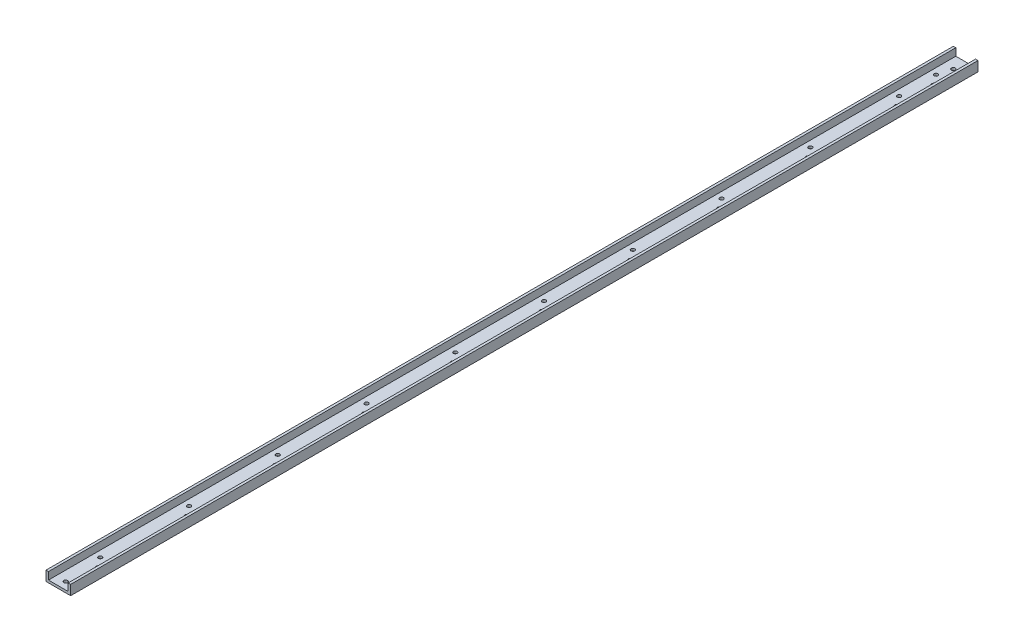
SolidWorks part; units mm, degrees
ref_plane "Front Plane" through (0, 0, 0) normal (0, 0, 1) x (1, 0, 0)
ref_plane "Top Plane" through (0, 0, 0) normal (0, 1, 0) x (1, 0, 0)
ref_plane "Right Plane" through (0, 0, 0) normal (1, 0, 0) x (0, 0, -1)
sketch "Sketch1" plane through (0, 0, 0) normal (0, 0, 1) x (1, 0, 0)
  line L0 (3.175, 3.175) -> (3.175, 12.7)
  line L1 (0, 0) -> (31.75, 0)
  line L2 (0, 0) -> (0, 12.7)
  line L4 (31.75, 0) -> (31.75, 12.7)
  line L5 (3.175, 3.175) -> (28.575, 3.175)
  line L6 (28.575, 3.175) -> (28.575, 12.7)
  line L7 (0, 12.7) -> (3.175, 12.7)
  line L8 (31.75, 12.7) -> (28.575, 12.7)
  dimension "D1" = 31.75
  dimension "D2" = 12.7
  dimension "D3" = 3.175
extrude "Boss-Extrude1" add sketch "Sketch1" along normal blind 1168.4
sketch "Sketch3" plane through (0, 3.175, 0) normal (0, 1, 0) x (1, 0, 0)
  line L0 (11.1125, -1109.6625) -> (11.1125, -1122.3625) construction
  line L1 (11.1125, -1122.3625) -> (20.6375, -1122.3625) construction
  line L2 (20.6375, -1122.3625) -> (11.1125, -1109.6625) construction
  line L3 (20.6375, -1122.3625) -> (20.6375, -1168.4) construction
  line L4 (28.575, -1168.4) -> (3.175, -1168.4) construction
  circle A1 centre (11.1125, -1109.6625) radius 2.413
  circle A3 centre (20.6375, -1122.3625) radius 2.413
  dimension "D1" = 9.525
  dimension "D2" = 12.7
  dimension "D3" = 46.0375
extrude "Cut-Extrude1" cut sketch "Sketch3" against normal up to next
sketch "Sketch4" plane through (0, 3.175, 0) normal (0, 1, 0) x (1, 0, 0)
  line L0 (15.875, -1168.4) -> (15.875, -1158.875) construction
  line L1 (28.575, -1168.4) -> (3.175, -1168.4) construction
  circle A0 centre (15.875, -1158.875) radius 2.413
  dimension "D2" = 4.826
  dimension "D1" = 9.525
extrude "Cut-Extrude2" cut sketch "Sketch4" against normal up to next
pattern_linear "LPattern1" count 10 spacing 114.3 along (0, 0, -1) of "Cut-Extrude1"
sketch "Sketch5" plane through (0, 0, 0) normal (0, -1, 0) x (1, 0, 0)
  circle A0 centre (11.1125, 33.3375) radius 2.413 construction
  circle A1 centre (11.1125, 33.3375) radius 2.413
  circle A2 centre (20.6375, 46.0375) radius 2.413 construction
  circle A3 centre (20.6375, 46.0375) radius 2.413
extrude "Cut-Extrude3" cut sketch "Sketch5" against normal up to next
sketch "Sketch6" plane through (0, 3.175, 0) normal (0, 1, 0) x (1, 0, 0)
  line L0 (15.875, 0) -> (15.875, -15.875) construction
  line L1 (28.575, 0) -> (3.175, 0) construction
  circle A0 centre (15.875, -15.875) radius 2.413
  dimension "D2" = 4.826
  dimension "D1" = 15.875
extrude "Cut-Extrude4" cut sketch "Sketch6" against normal up to next
